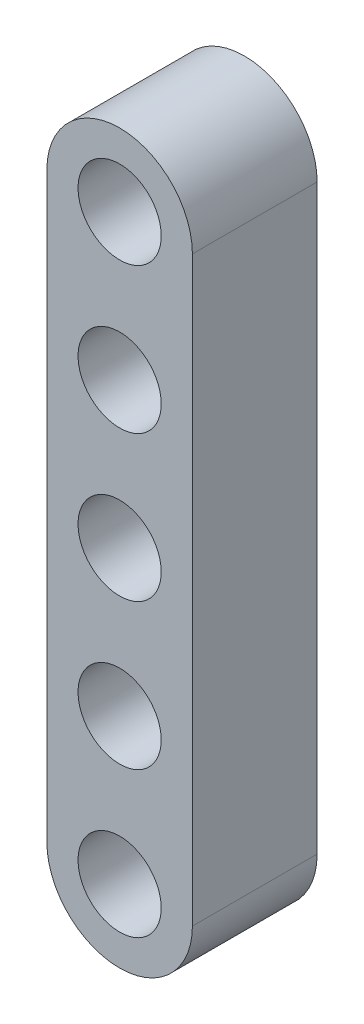
SolidWorks part; units mm, degrees
ref_plane "Front Plane" through (0, 0, 0) normal (0, 0, 1) x (1, 0, 0)
ref_plane "Top Plane" through (0, 0, 0) normal (0, 1, 0) x (1, 0, 0)
ref_plane "Right Plane" through (0, 0, 0) normal (1, 0, 0) x (0, 0, -1)
sketch "Sketch1" plane through (0, 0, 0) normal (0, 0, 1) x (1, 0, 0)
  line L0 (0, 0) -> (0, 87.443) construction
  line L1 (0, 0) -> (0, 28) construction
  line L2 (-3.5, 0) -> (-3.5, 28)
  line L3 (3.5, 0) -> (3.5, 28)
  circle A0 centre (0, 0) radius 2
  circle A1 centre (0, 7) radius 2
  circle A2 centre (0, 14) radius 2
  circle A3 centre (0, 21) radius 2
  circle A4 centre (0, 28) radius 2
  arc A14 (-3.5, 0) -> (3.5, 0) centre (0, 0) ccw
  arc A15 (3.5, 28) -> (-3.5, 28) centre (0, 28) ccw
  circle A16 centre (0, 91) radius 2 [skipped]
  circle A17 centre (0, 84) radius 2 [skipped]
  circle A18 centre (0, 77) radius 2 [skipped]
  circle A19 centre (0, 35) radius 2 [skipped]
  circle A20 centre (0, 42) radius 2 [skipped]
  circle A21 centre (0, 56) radius 2 [skipped]
  circle A22 centre (0, 49) radius 2 [skipped]
  circle A23 centre (0, 63) radius 2 [skipped]
  circle A24 centre (0, 70) radius 2 [skipped]
  point P3 (0, 14)
  dimension "D1" = 4
  dimension "D4" = 28
  dimension "D3" = 7
  dimension "D2" = 14
extrude "Boss-Extrude1" add sketch "Sketch1" along normal blind 6
